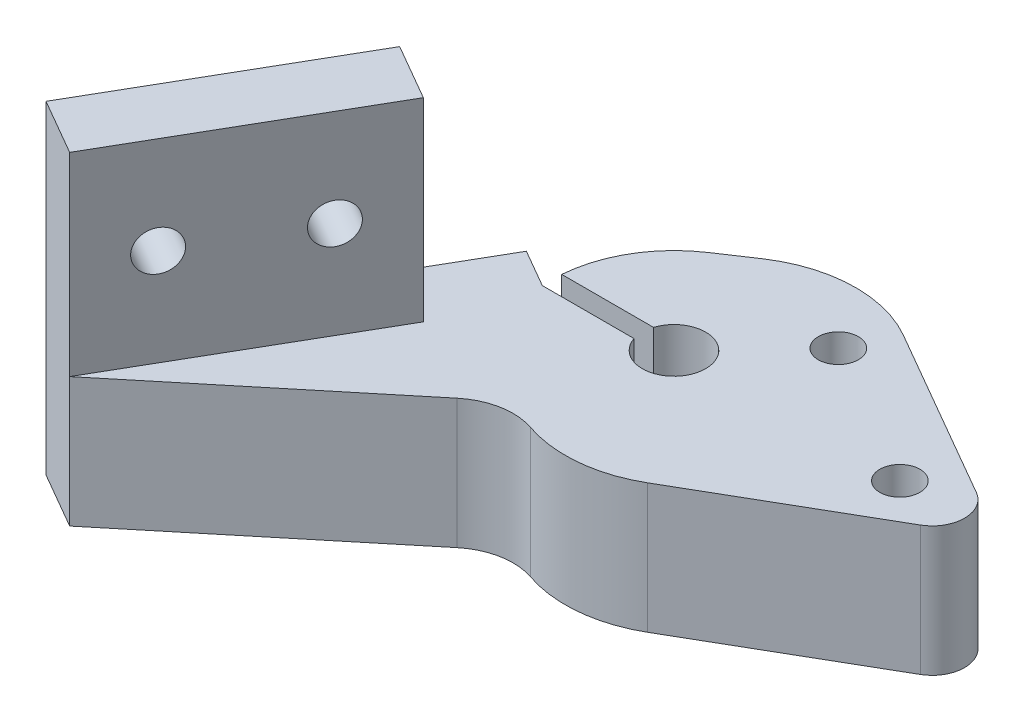
SolidWorks part; units mm, degrees
ref_plane "Front Plane" through (0, 0, 0) normal (0, 0, 1) x (1, 0, 0)
ref_plane "Top Plane" through (0, 0, 0) normal (0, 1, 0) x (1, 0, 0)
ref_plane "Right Plane" through (0, 0, 0) normal (1, 0, 0) x (0, 0, -1)
sketch "Sketch1" plane through (0, 0, 0) normal (0, 1, 0) x (1, 0, 0)
  line L0 (-7.5, -12.9904) -> (-3.75, -6.4952) construction
  line L1 (11.25, 2.1651) -> (-2.1212, 9.8849)
  line L2 (-7.5, 12.9904) -> (-7.5, -12.9904) construction
  line L3 (-2.1212, -9.8849) -> (11.25, -2.1651)
  line L4 (-7.5, 12.9904) -> (-3.75, 6.4952) construction
  line L5 (0, 0) -> (-7.5, 0) construction
  line L7 (-12.6679, -9.5454) -> (-15.1916, -7.8631)
  line L8 (-12.6679, 9.5454) -> (-15.1916, 7.8631)
  circle A0 centre (0, 0) radius 7.5 construction
  circle A1 centre (7.5, 0) radius 1.55
  circle A2 centre (-3.75, -6.4952) radius 1.55 construction
  circle A3 centre (-3.75, 6.4952) radius 1.55
  circle A4 centre (-9.95, 0) radius 2.45
  arc A5 (-15.1916, 7.8631) -> (-15.1916, -7.8631) centre (-9.95, 0) ccw
  arc A6 (-12.6679, -9.5454) -> (-2.1212, -9.8849) centre (-7.1212, -1.2247) ccw
  arc A7 (-2.1212, 9.8849) -> (-12.6679, 9.5454) centre (-7.1212, 1.2247) ccw
  arc A8 (11.25, 2.1651) -> (11.25, -2.1651) centre (10, 0) cw
  dimension "D2" = 3.1
  dimension "D3" = 4.9
  dimension "D4" = 7
  dimension "D5" = 10
  dimension "D6" = 2.5
  dimension "D1" = 7.5
extrude "Boss-Extrude1" add sketch "Sketch1" along normal blind 10
sketch "Sketch2" plane through (0, 10, 0) normal (0, 1, 0) x (1, 0, 0)
  line L0 (-9.95, 0.75) -> (-9.95, -0.75)
  line L1 (-9.95, 0.75) -> (-19.4, 0.75)
  line L2 (-9.95, -0.75) -> (-19.4, -0.75)
  line L3 (-19.4, 0.75) -> (-19.4, -0.75)
  arc A0 (-15.1916, 7.8631) -> (-15.1916, -7.8631) centre (-9.95, 0) ccw construction
  point P0 (-9.95, 0)
  dimension "D1" = 1.5
extrude "Cut-Extrude1" cut sketch "Sketch2" against normal through all
sketch "Sketch3" plane through (0, 0, 0) normal (0, -1, 0) x (1, 0, 0)
  line L0 (-22.286, -0.9334) -> (-35.8687, 22.5925)
  line L1 (-35.8687, 22.5925) -> (-31.5386, 25.0925)
  line L2 (-31.5386, 25.0925) -> (-12.6679, 9.5454)
  line L3 (7.5, 0) -> (-3.75, -6.4952) construction
  line L4 (-19.3702, 0.75) -> (-22.286, -0.9334)
  line L6 (-12.6679, 9.5454) -> (-24.4189, 2.7609) construction
  dimension "D1" = 3.3669
  dimension "D2" = 22.8995
  dimension "D3" = 5
extrude "Boss-Extrude3" add sketch "Sketch3" against normal up to surface (10 mm away) up to face at (-8.0388, 10, 0)
sketch "Sketch4" plane through (0, 10, 0) normal (0, 1, 0) x (1, 0, 0)
  line L0 (-35.8687, -22.5925) -> (-25.8687, -5.272)
  line L1 (-35.8687, -22.5925) -> (-31.5386, -25.0925)
  line L2 (-25.8687, -5.272) -> (-21.5386, -7.772)
  line L3 (-31.5386, -25.0925) -> (-21.5386, -7.772)
  line L4 (-22.286, 0.9334) -> (-35.8687, -22.5925) construction
  dimension "D1" = 20
  dimension "D2" = 5
extrude "Boss-Extrude4" add sketch "Sketch4" along normal blind 15
hole_wizard "Ø3.0mm Clearance Dowel Hole1" positions "Sketch8" profile "Sketch7" hole size "Ø3.0" standard "DIN" end condition through all
sketch "Sketch8" plane through (-12.7886, 0, -7.3835) normal (0.866, 0, 0.5) x (0.5, 0, -0.866)
  line L0 (-27.5, 25) -> (-27.5, 10) construction
  line L1 (-37.5, 25) -> (-17.5, 25) construction
  line L2 (-37.5, 10) -> (-17.5, 10) construction
  point P9 (-32.5, 17.5)
  point P11 (-22.5, 17.5)
  dimension "D1" = 5
  dimension "D2" = 5
  dimension "D3" = 7.5
  dimension "D4" = 7.5
sketch "Sketch7" plane through (-29.0386, 17.5, 20.7623) normal (0, 1, 0) x (0.5, 0, -0.866)
  line L0 (0, 0) -> (0, 21.9086)
  line L1 (0, 21.9086) -> (1.554, 21.9086)
  line L2 (1.554, 21.9086) -> (1.554, 0)
  line L5 (1.554, 0) -> (0, 0)
  line L11 (0, -6.35) -> (0, 107.95) construction
  dimension "Thru Hole Dia." = 3.108
  dimension "Thru Hole Depth" = 21.9086
fillet "Fillet1" radius 5 1 edges at (-12.6679, 5, 9.5454)
